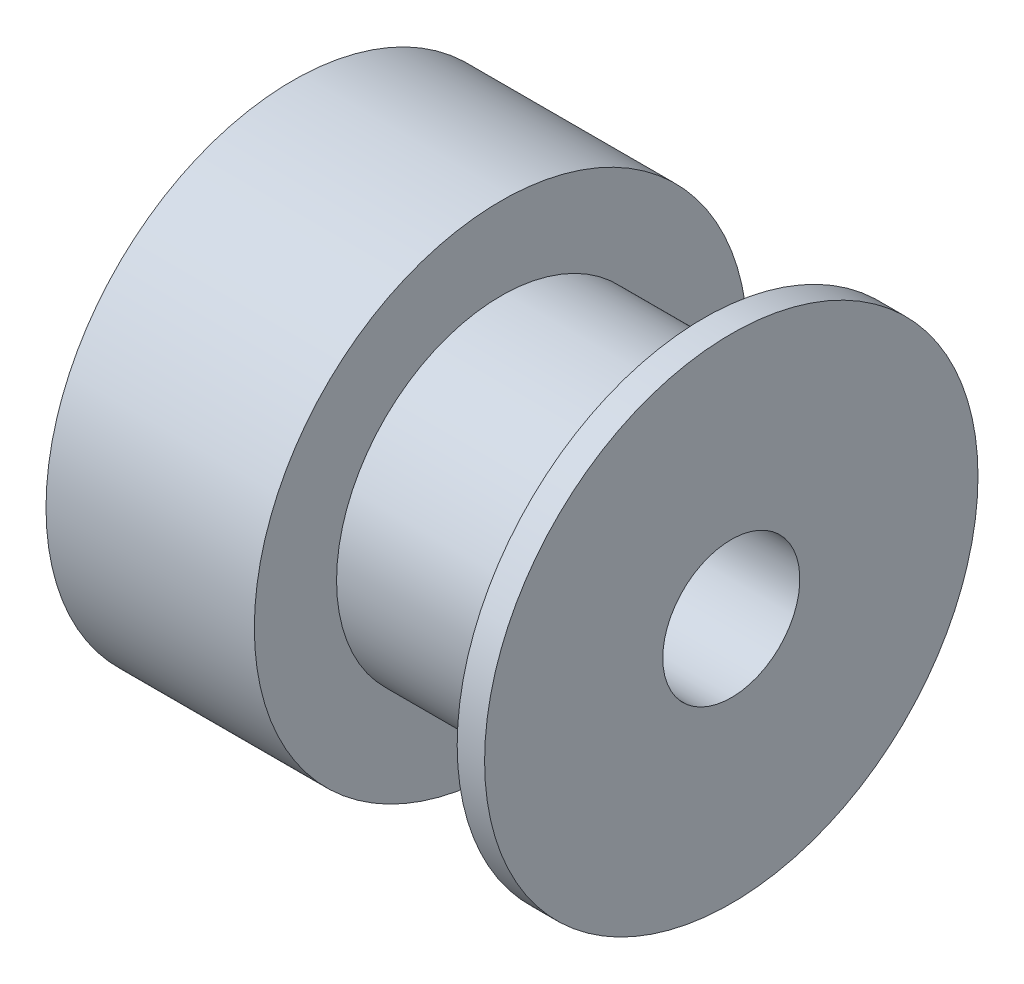
SolidWorks part; units mm, degrees
material "5052-H32"
ref_plane "Ön Düzlem" through (0, 0, 0) normal (0, 0, 1) x (1, 0, 0)
ref_plane "Üst Düzlem" through (0, 0, 0) normal (0, 1, 0) x (1, 0, 0)
ref_plane "Sağ Düzlem" through (0, 0, 0) normal (1, 0, 0) x (0, 0, -1)
sketch "Çizim1" plane through (0, 0, 0) normal (0, 0, 1) x (1, 0, 0)
  line L0 (-5.1809, 0) -> (9.6627, 0) construction
  line L1 (-0.4, 9) -> (-0.4, 6)
  line L4 (8, 9) -> (7, 9)
  line L5 (-8, 2.5) -> (-8, 9)
  line L6 (8, -9) -> (-8, 9) construction
  line L7 (8, 9) -> (-8, -9) construction
  line L8 (-0.4, 6) -> (7, 6)
  line L9 (7, 6) -> (7, 9)
  line L10 (-8, 2.5) -> (8, 2.5)
  line L11 (8, 2.5) -> (8, 9)
  line L12 (-0.4, 9) -> (-8, 9)
  point P3 (0, 0)
  dimension "D1" = 18
  dimension "D2" = 16
  dimension "D4" = 3
  dimension "D5" = 7.4
  dimension "D6" = 2.5
revolve "Döndür1" add sketch "Çizim1" angle 360 about L0
sketch "Sketch1" plane through (0, 0, 0) normal (0, 0, 1) x (1, 0, 0)
  line L0 (0, 0) -> (14.3828, 0)
